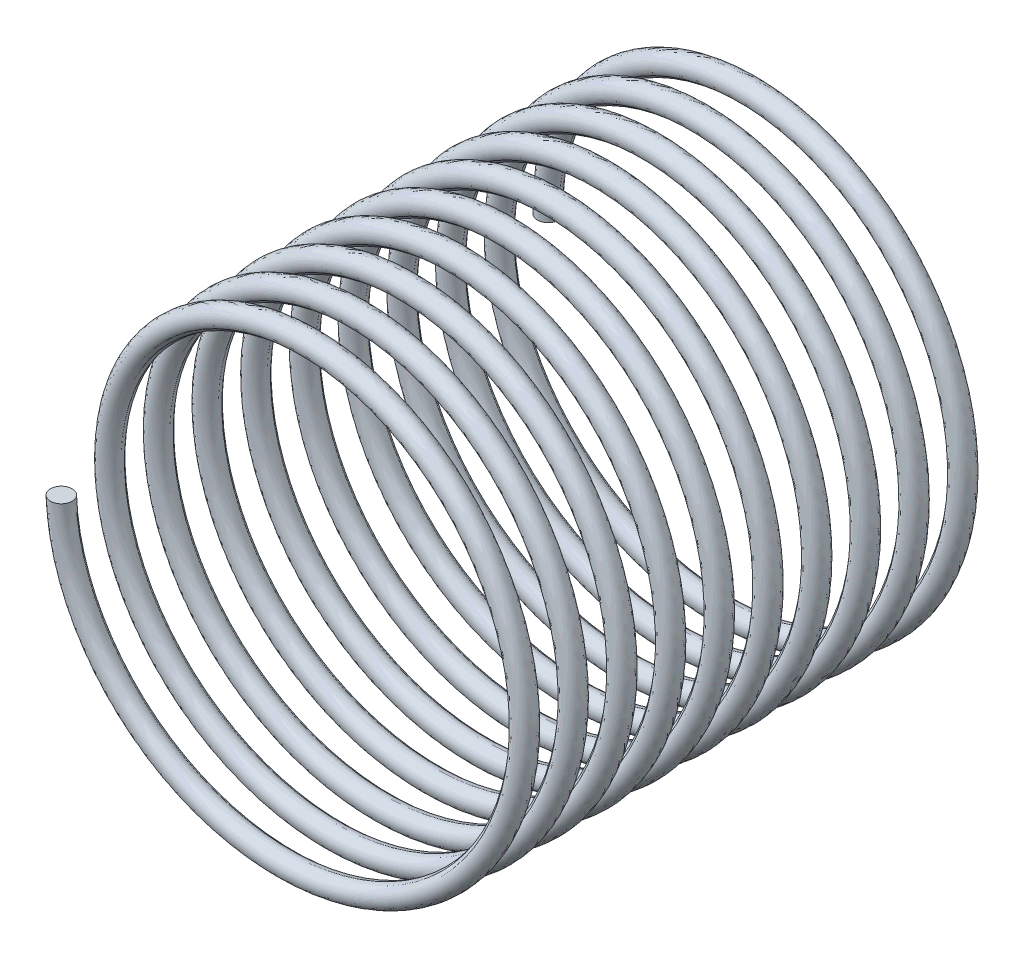
SolidWorks part; units mm, degrees
material "AISI 316 Stainless Steel Sheet (SS)"
ref_plane "Front Plane" through (0, 0, 0) normal (0, 0, 1) x (1, 0, 0)
ref_plane "Top Plane" through (0, 0, 0) normal (0, 1, 0) x (1, 0, 0)
ref_plane "Right Plane" through (0, 0, 0) normal (1, 0, 0) x (0, 0, -1)
sketch "Sketch1" plane through (0, 0, 0) normal (0, 0, 1) x (1, 0, 0)
  circle A0 centre (0, 0) radius 105
  dimension "D1" = 210
curve "Helix/Spiral1" pitch 22.45 height 224.5 turns 10
sketch "Sketch2" plane through (0, 0, 0) normal (0, 1, 0) x (1, 0, 0)
  circle A0 centre (-101.1357, -223.5276) radius 4.9871
  spline S0 degree 3 poles (-105, 0) (-105, -0.1643) (-104.3315, -0.4935) (-101.3424, -0.9868) (-96.4238, -1.4802) (-89.6694, -1.9736) (-81.2078, -2.467) (-71.2, -2.9604) (-59.8367, -3.4538) (-47.3341, -3.9473) (-33.9303, -4.4407) (-19.8805, -4.9341) (-5.4522, -5.4275) (9.0799, -5.9209) (23.4391, -6.4143) (37.352, -6.9077) (50.5539, -7.4011) (62.7932, -7.8945) (73.837, -8.3879) (83.4749, -8.8813) (91.5237, -9.3747) (97.8298, -9.8681) (102.2734, -10.3615) (104.7698, -10.8549) (105.2715, -11.3484) (103.7689, -11.8418) (100.2906, -12.3352) (94.9029, -12.8286) (87.7083, -13.322) (78.8438, -13.8154) (68.4782, -14.3088) (56.8089, -14.8022) (44.0579, -15.2956) (30.4682, -15.789) (16.2983, -16.2824) (1.8181, -16.7758) (-12.6966, -17.2692) (-26.9697, -17.7626) (-40.7292, -18.256) (-53.7134, -18.7495) (-65.6748, -19.2429) (-76.3859, -19.7363) (-85.6427, -20.2297) (-93.2688, -20.7231) (-99.1193, -21.2165) (-103.0826, -21.7099) (-105.0833, -22.2033) (-105.0833, -22.6967) (-103.0826, -23.1901) (-99.1193, -23.6835) (-93.2688, -24.1769) (-85.6427, -24.6703) (-76.3859, -25.1637) (-65.6748, -25.6571) (-53.7134, -26.1505) (-40.7292, -26.644) (-26.9697, -27.1374) (-12.6966, -27.6308) (1.8181, -28.1242) (16.2983, -28.6176) (30.4682, -29.111) (44.0579, -29.6044) (56.8089, -30.0978) (68.4782, -30.5912) (78.8438, -31.0846) (87.7083, -31.578) (94.9029, -32.0714) (100.2906, -32.5648) (103.7689, -33.0582) (105.2715, -33.5516) (104.7698, -34.0451) (102.2734, -34.5385) (97.8298, -35.0319) (91.5237, -35.5253) (83.4749, -36.0187) (73.837, -36.5121) (62.7932, -37.0055) (50.5539, -37.4989) (37.352, -37.9923) (23.4391, -38.4857) (9.0799, -38.9791) (-5.4522, -39.4725) (-19.8805, -39.9659) (-33.9303, -40.4593) (-47.3341, -40.9527) (-59.8367, -41.4462) (-71.2, -41.9396) (-81.2078, -42.433) (-89.6694, -42.9264) (-96.4238, -43.4198) (-101.3424, -43.9132) (-104.3315, -44.4066) (-105.3342, -44.9) (-104.3315, -45.3934) (-101.3424, -45.8868) (-96.4238, -46.3802) (-89.6694, -46.8736) (-81.2078, -47.367) (-71.2, -47.8604) (-59.8367, -48.3538) (-47.3341, -48.8473) (-33.9303, -49.3407) (-19.8805, -49.8341) (-5.4522, -50.3275) (9.0799, -50.8209) (23.4391, -51.3143) (37.352, -51.8077) (50.5539, -52.3011) (62.7932, -52.7945) (73.837, -53.2879) (83.4749, -53.7813) (91.5237, -54.2747) (97.8298, -54.7681) (102.2734, -55.2615) (104.7698, -55.7549) (105.2715, -56.2484) (103.7689, -56.7418) (100.2906, -57.2352) (94.9029, -57.7286) (87.7083, -58.222) (78.8438, -58.7154) (68.4782, -59.2088) (56.8089, -59.7022) (44.0579, -60.1956) (30.4682, -60.689) (16.2983, -61.1824) (1.8181, -61.6758) (-12.6966, -62.1692) (-26.9697, -62.6626) (-40.7292, -63.156) (-53.7134, -63.6495) (-65.6748, -64.1429) (-76.3859, -64.6363) (-85.6427, -65.1297) (-93.2688, -65.6231) (-99.1193, -66.1165) (-103.0826, -66.6099) (-105.0833, -67.1033) (-105.0833, -67.5967) (-103.0826, -68.0901) (-99.1193, -68.5835) (-93.2688, -69.0769) (-85.6427, -69.5703) (-76.3859, -70.0637) (-65.6748, -70.5571) (-53.7134, -71.0505) (-40.7292, -71.544) (-26.9697, -72.0374) (-12.6966, -72.5308) (1.8181, -73.0242) (16.2983, -73.5176) (30.4682, -74.011) (44.0579, -74.5044) (56.8089, -74.9978) (68.4782, -75.4912) (78.8438, -75.9846) (87.7083, -76.478) (94.9029, -76.9714) (100.2906, -77.4648) (103.7689, -77.9582) (105.2715, -78.4516) (104.7698, -78.9451) (102.2734, -79.4385) (97.8298, -79.9319) (91.5237, -80.4253) (83.4749, -80.9187) (73.837, -81.4121) (62.7932, -81.9055) (50.5539, -82.3989) (37.352, -82.8923) (23.4391, -83.3857) (9.0799, -83.8791) (-5.4522, -84.3725) (-19.8805, -84.8659) (-33.9303, -85.3593) (-47.3341, -85.8527) (-59.8367, -86.3462) (-71.2, -86.8396) (-81.2078, -87.333) (-89.6694, -87.8264) (-96.4238, -88.3198) (-101.3424, -88.8132) (-104.3315, -89.3066) (-105.3342, -89.8) (-104.3315, -90.2934) (-101.3424, -90.7868) (-96.4238, -91.2802) (-89.6694, -91.7736) (-81.2078, -92.267) (-71.2, -92.7604) (-59.8367, -93.2538) (-47.3341, -93.7473) (-33.9303, -94.2407) (-19.8805, -94.7341) (-5.4522, -95.2275) (9.0799, -95.7209) (23.4391, -96.2143) (37.352, -96.7077) (50.5539, -97.2011) (62.7932, -97.6945) (73.837, -98.1879) (83.4749, -98.6813) (91.5237, -99.1747) (97.8298, -99.6681) (102.2734, -100.1615) (104.7698, -100.6549) (105.2715, -101.1484) (103.7689, -101.6418) (100.2906, -102.1352) (94.9029, -102.6286) (87.7083, -103.122) (78.8438, -103.6154) (68.4782, -104.1088) (56.8089, -104.6022) (44.0579, -105.0956) (30.4682, -105.589) (16.2983, -106.0824) (1.8181, -106.5758) (-12.6966, -107.0692) (-26.9697, -107.5626) (-40.7292, -108.056) (-53.7134, -108.5495) (-65.6748, -109.0429) (-76.3859, -109.5363) (-85.6427, -110.0297) (-93.2688, -110.5231) (-99.1193, -111.0165) (-103.0826, -111.5099) (-105.0833, -112.0033) (-105.0833, -112.4967) (-103.0826, -112.9901) (-99.1193, -113.4835) (-93.2688, -113.9769) (-85.6427, -114.4703) (-76.3859, -114.9637) (-65.6748, -115.4571) (-53.7134, -115.9505) (-40.7292, -116.444) (-26.9697, -116.9374) (-12.6966, -117.4308) (1.8181, -117.9242) (16.2983, -118.4176) (30.4682, -118.911) (44.0579, -119.4044) (56.8089, -119.8978) (68.4782, -120.3912) (78.8438, -120.8846) (87.7083, -121.378) (94.9029, -121.8714) (100.2906, -122.3648) (103.7689, -122.8582) (105.2715, -123.3516) (104.7698, -123.8451) (102.2734, -124.3385) (97.8298, -124.8319) (91.5237, -125.3253) (83.4749, -125.8187) (73.837, -126.3121) (62.7932, -126.8055) (50.5539, -127.2989) (37.352, -127.7923) (23.4391, -128.2857) (9.0799, -128.7791) (-5.4522, -129.2725) (-19.8805, -129.7659) (-33.9303, -130.2593) (-47.3341, -130.7527) (-59.8367, -131.2462) (-71.2, -131.7396) (-81.2078, -132.233) (-89.6694, -132.7264) (-96.4238, -133.2198) (-101.3424, -133.7132) (-104.3315, -134.2066) (-105.3342, -134.7) (-104.3315, -135.1934) (-101.3424, -135.6868) (-96.4238, -136.1802) (-89.6694, -136.6736) (-81.2078, -137.167) (-71.2, -137.6604) (-59.8367, -138.1538) (-47.3341, -138.6473) (-33.9303, -139.1407) (-19.8805, -139.6341) (-5.4522, -140.1275) (9.0799, -140.6209) (23.4391, -141.1143) (37.352, -141.6077) (50.5539, -142.1011) (62.7932, -142.5945) (73.837, -143.0879) (83.4749, -143.5813) (91.5237, -144.0747) (97.8298, -144.5681) (102.2734, -145.0615) (104.7698, -145.5549) (105.2715, -146.0484) (103.7689, -146.5418) (100.2906, -147.0352) (94.9029, -147.5286) (87.7083, -148.022) (78.8438, -148.5154) (68.4782, -149.0088) (56.8089, -149.5022) (44.0579, -149.9956) (30.4682, -150.489) (16.2983, -150.9824) (1.8181, -151.4758) (-12.6966, -151.9692) (-26.9697, -152.4626) (-40.7292, -152.956) (-53.7134, -153.4495) (-65.6748, -153.9429) (-76.3859, -154.4363) (-85.6427, -154.9297) (-93.2688, -155.4231) (-99.1193, -155.9165) (-103.0826, -156.4099) (-105.0833, -156.9033) (-105.0833, -157.3967) (-103.0826, -157.8901) (-99.1193, -158.3835) (-93.2688, -158.8769) (-85.6427, -159.3703) (-76.3859, -159.8637) (-65.6748, -160.3571) (-53.7134, -160.8505) (-40.7292, -161.344) (-26.9697, -161.8374) (-12.6966, -162.3308) (1.8181, -162.8242) (16.2983, -163.3176) (30.4682, -163.811) (44.0579, -164.3044) (56.8089, -164.7978) (68.4782, -165.2912) (78.8438, -165.7846) (87.7083, -166.278) (94.9029, -166.7714) (100.2906, -167.2648) (103.7689, -167.7582) (105.2715, -168.2516) (104.7698, -168.7451) (102.2734, -169.2385) (97.8298, -169.7319) (91.5237, -170.2253) (83.4749, -170.7187) (73.837, -171.2121) (62.7932, -171.7055) (50.5539, -172.1989) (37.352, -172.6923) (23.4391, -173.1857) (9.0799, -173.6791) (-5.4522, -174.1725) (-19.8805, -174.6659) (-33.9303, -175.1593) (-47.3341, -175.6527) (-59.8367, -176.1462) (-71.2, -176.6396) (-81.2078, -177.133) (-89.6694, -177.6264) (-96.4238, -178.1198) (-101.3424, -178.6132) (-104.3315, -179.1066) (-105.3342, -179.6) (-104.3315, -180.0934) (-101.3424, -180.5868) (-96.4238, -181.0802) (-89.6694, -181.5736) (-81.2078, -182.067) (-71.2, -182.5604) (-59.8367, -183.0538) (-47.3341, -183.5473) (-33.9303, -184.0407) (-19.8805, -184.5341) (-5.4522, -185.0275) (9.0799, -185.5209) (23.4391, -186.0143) (37.352, -186.5077) (50.5539, -187.0011) (62.7932, -187.4945) (73.837, -187.9879) (83.4749, -188.4813) (91.5237, -188.9747) (97.8298, -189.4681) (102.2734, -189.9615) (104.7698, -190.4549) (105.2715, -190.9484) (103.7689, -191.4418) (100.2906, -191.9352) (94.9029, -192.4286) (87.7083, -192.922) (78.8438, -193.4154) (68.4782, -193.9088) (56.8089, -194.4022) (44.0579, -194.8956) (30.4682, -195.389) (16.2983, -195.8824) (1.8181, -196.3758) (-12.6966, -196.8692) (-26.9697, -197.3626) (-40.7292, -197.856) (-53.7134, -198.3495) (-65.6748, -198.8429) (-76.3859, -199.3363) (-85.6427, -199.8297) (-93.2688, -200.3231) (-99.1193, -200.8165) (-103.0826, -201.3099) (-105.0833, -201.8033) (-105.0833, -202.2967) (-103.0826, -202.7901) (-99.1193, -203.2835) (-93.2688, -203.7769) (-85.6427, -204.2703) (-76.3859, -204.7637) (-65.6748, -205.2571) (-53.7134, -205.7505) (-40.7292, -206.244) (-26.9697, -206.7374) (-12.6966, -207.2308) (1.8181, -207.7242) (16.2983, -208.2176) (30.4682, -208.711) (44.0579, -209.2044) (56.8089, -209.6978) (68.4782, -210.1912) (78.8438, -210.6846) (87.7083, -211.178) (94.9029, -211.6714) (100.2906, -212.1648) (103.7689, -212.6582) (105.2715, -213.1516) (104.7698, -213.6451) (102.2734, -214.1385) (97.8298, -214.6319) (91.5237, -215.1253) (83.4749, -215.6187) (73.837, -216.1121) (62.7932, -216.6055) (50.5539, -217.0989) (37.352, -217.5923) (23.4391, -218.0857) (9.0799, -218.5791) (-5.4522, -219.0725) (-19.8805, -219.5659) (-33.9303, -220.0593) (-47.3341, -220.5527) (-59.8367, -221.0462) (-71.2, -221.5396) (-81.2078, -222.033) (-89.6694, -222.5264) (-96.4238, -223.0198) (-101.3424, -223.5132) (-104.3315, -224.0065) (-105, -224.3357) (-105, -224.5) knots 0 0 0 0 0.002198 0.004396 0.006593 0.008791 0.010989 0.013187 0.015385 0.017582 0.01978 0.021978 0.024176 0.026374 0.028571 0.030769 0.032967 0.035165 0.037363 0.03956 0.041758 0.043956 0.046154 0.048352 0.050549 0.052747 0.054945 0.057143 0.059341 0.061538 0.063736 0.065934 0.068132 0.07033 0.072527 0.074725 0.076923 0.079121 0.081319 0.083516 0.085714 0.087912 0.09011 0.092308 0.094505 0.096703 0.098901 0.101099 0.103297 0.105495 0.107692 0.10989 0.112088 0.114286 0.116484 0.118681 0.120879 0.123077 0.125275 0.127473 0.12967 0.131868 0.134066 0.136264 0.138462 0.140659 0.142857 0.145055 0.147253 0.149451 0.151648 0.153846 0.156044 0.158242 0.16044 0.162637 0.164835 0.167033 0.169231 0.171429 0.173626 0.175824 0.178022 0.18022 0.182418 0.184615 0.186813 0.189011 0.191209 0.193407 0.195604 0.197802 0.2 0.202198 0.204396 0.206593 0.208791 0.210989 0.213187 0.215385 0.217582 0.21978 0.221978 0.224176 0.226374 0.228571 0.230769 0.232967 0.235165 0.237363 0.23956 0.241758 0.243956 0.246154 0.248352 0.250549 0.252747 0.254945 0.257143 0.259341 0.261538 0.263736 0.265934 0.268132 0.27033 0.272527 0.274725 0.276923 0.279121 0.281319 0.283516 0.285714 0.287912 0.29011 0.292308 0.294505 0.296703 0.298901 0.301099 0.303297 0.305495 0.307692 0.30989 0.312088 0.314286 0.316484 0.318681 0.320879 0.323077 0.325275 0.327473 0.32967 0.331868 0.334066 0.336264 0.338462 0.340659 0.342857 0.345055 0.347253 0.349451 0.351648 0.353846 0.356044 0.358242 0.36044 0.362637 0.364835 0.367033 0.369231 0.371429 0.373626 0.375824 0.378022 0.38022 0.382418 0.384615 0.386813 0.389011 0.391209 0.393407 0.395604 0.397802 0.4 0.402198 0.404396 0.406593 0.408791 0.410989 0.413187 0.415385 0.417582 0.41978 0.421978 0.424176 0.426374 0.428571 0.430769 0.432967 0.435165 0.437363 0.43956 0.441758 0.443956 0.446154 0.448352 0.450549 0.452747 0.454945 0.457143 0.459341 0.461538 0.463736 0.465934 0.468132 0.47033 0.472527 0.474725 0.476923 0.479121 0.481319 0.483516 0.485714 0.487912 0.49011 0.492308 0.494505 0.496703 0.498901 0.501099 0.503297 0.505495 0.507692 0.50989 0.512088 0.514286 0.516484 0.518681 0.520879 0.523077 0.525275 0.527473 0.52967 0.531868 0.534066 0.536264 0.538462 0.540659 0.542857 0.545055 0.547253 0.549451 0.551648 0.553846 0.556044 0.558242 0.56044 0.562637 0.564835 0.567033 0.569231 0.571429 0.573626 0.575824 0.578022 0.58022 0.582418 0.584615 0.586813 0.589011 0.591209 0.593407 0.595604 0.597802 0.6 0.602198 0.604396 0.606593 0.608791 0.610989 0.613187 0.615385 0.617582 0.61978 0.621978 0.624176 0.626374 0.628571 0.630769 0.632967 0.635165 0.637363 0.63956 0.641758 0.643956 0.646154 0.648352 0.650549 0.652747 0.654945 0.657143 0.659341 0.661538 0.663736 0.665934 0.668132 0.67033 0.672527 0.674725 0.676923 0.679121 0.681319 0.683516 0.685714 0.687912 0.69011 0.692308 0.694505 0.696703 0.698901 0.701099 0.703297 0.705495 0.707692 0.70989 0.712088 0.714286 0.716484 0.718681 0.720879 0.723077 0.725275 0.727473 0.72967 0.731868 0.734066 0.736264 0.738462 0.740659 0.742857 0.745055 0.747253 0.749451 0.751648 0.753846 0.756044 0.758242 0.76044 0.762637 0.764835 0.767033 0.769231 0.771429 0.773626 0.775824 0.778022 0.78022 0.782418 0.784615 0.786813 0.789011 0.791209 0.793407 0.795604 0.797802 0.8 0.802198 0.804396 0.806593 0.808791 0.810989 0.813187 0.815385 0.817582 0.81978 0.821978 0.824176 0.826374 0.828571 0.830769 0.832967 0.835165 0.837363 0.83956 0.841758 0.843956 0.846154 0.848352 0.850549 0.852747 0.854945 0.857143 0.859341 0.861538 0.863736 0.865934 0.868132 0.87033 0.872527 0.874725 0.876923 0.879121 0.881319 0.883516 0.885714 0.887912 0.89011 0.892308 0.894505 0.896703 0.898901 0.901099 0.903297 0.905495 0.907692 0.90989 0.912088 0.914286 0.916484 0.918681 0.920879 0.923077 0.925275 0.927473 0.92967 0.931868 0.934066 0.936264 0.938462 0.940659 0.942857 0.945055 0.947253 0.949451 0.951648 0.953846 0.956044 0.958242 0.96044 0.962637 0.964835 0.967033 0.969231 0.971429 0.973626 0.975824 0.978022 0.98022 0.982418 0.984615 0.986813 0.989011 0.991209 0.993407 0.995604 0.997802 1 1 1 1 construction
sweep "Sweep1" add profiles "Sketch2" path "Helix/Spiral1"
